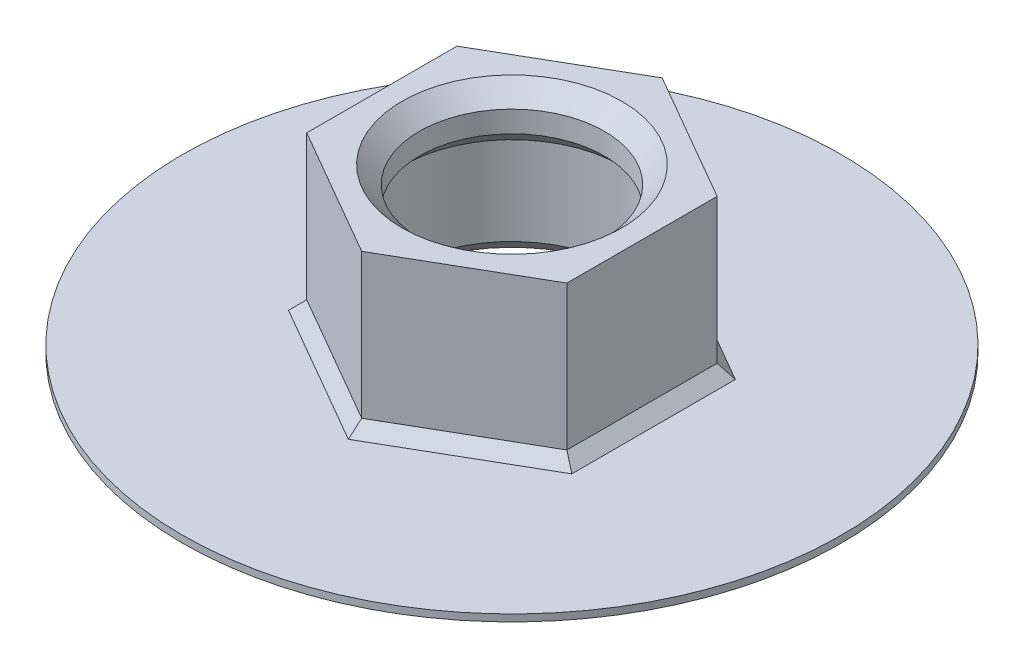
SolidWorks part; units mm, degrees
ref_plane "Front Plane" through (0, 0, 0) normal (0, 0, 1) x (1, 0, 0)
ref_plane "Top Plane" through (0, 0, 0) normal (0, 1, 0) x (1, 0, 0)
ref_plane "Right Plane" through (0, 0, 0) normal (1, 0, 0) x (0, 0, -1)
sketch "Sketch1" plane through (0, 0, 0) normal (0, 1, 0) x (1, 0, 0)
  circle A0 centre (0, 0) radius 27
  circle A1 centre (0, 0) radius 9.675
  dimension "D1" = 54
  dimension "D2" = 19.35
extrude "Boss-Extrude1" add sketch "Sketch1" along normal blind 0.6
sketch "Sketch2" plane through (0, 0.6, 0) normal (0, 1, 0) x (1, 0, 0)
  line L1 (0, 12.9904) -> (-11.25, 6.4952)
  line L2 (-11.25, 6.4952) -> (-11.25, -6.4952)
  line L3 (-11.25, -6.4952) -> (0, -12.9904)
  line L4 (0, -12.9904) -> (11.25, -6.4952)
  line L5 (11.25, -6.4952) -> (11.25, 6.4952)
  line L6 (11.25, 6.4952) -> (0, 12.9904)
  circle A0 centre (0, 0) radius 9.675 construction
  circle A1 centre (0, 0) radius 9.675
  circle A2 centre (0, 0) radius 11.25 construction
  dimension "D1" = 22.5
extrude "Boss-Extrude2" add sketch "Sketch2" along normal blind 13.5
sketch "Sketch3" plane through (0, 14.1, 0) normal (0, 1, 0) x (1, 0, 0)
  circle A0 centre (0, 0) radius 10.0435
  circle A1 centre (0, 0) radius 8
  dimension "D1" = 16
extrude "Boss-Extrude3" add sketch "Sketch3" against normal offset from surface (4.85 mm away) 9.25 up to face at (0, 0, 27)
chamfer "Chamfer1" distance 1.5 angle 45 3 edges at (0, 14.1, 8) (0, 9.25, 8) (0, 0, 9.675)
sketch "Sketch4" plane through (0, 0, 0) normal (0, -1, 0) x (1, 0, 0)
  circle A0 centre (0, 0) radius 28.5
  circle A1 centre (0, 0) radius 25
  dimension "D1" = 50
  dimension "D2" = 57
extrude "Boss-Extrude4" add sketch "Sketch4" along normal blind 1.9 and the other way up to surface other way up to face at (0, 0.6, 27)
chamfer "Chamfer3" distance 1 angle 45 6 edges at (5.625, 0.6, 9.7428) (11.25, 0.6, 0) (5.625, 0.6, -9.7428) (-5.625, 0.6, -9.7428) (-11.25, 0.6, 0) (-5.625, 0.6, 9.7428)
sketch "Sketch5" plane through (0, -1.9, 0) normal (0, -1, 0) x (1, 0, 0)
  circle A1 centre (0, 0) radius 28.5
  circle A2 centre (0, 0) radius 28.5
  dimension "D1" = 0
extrude "Cut-Extrude1" cut sketch "Sketch5" against normal up to surface (1.9 mm away) up to face at (0, 0, 11.175)
